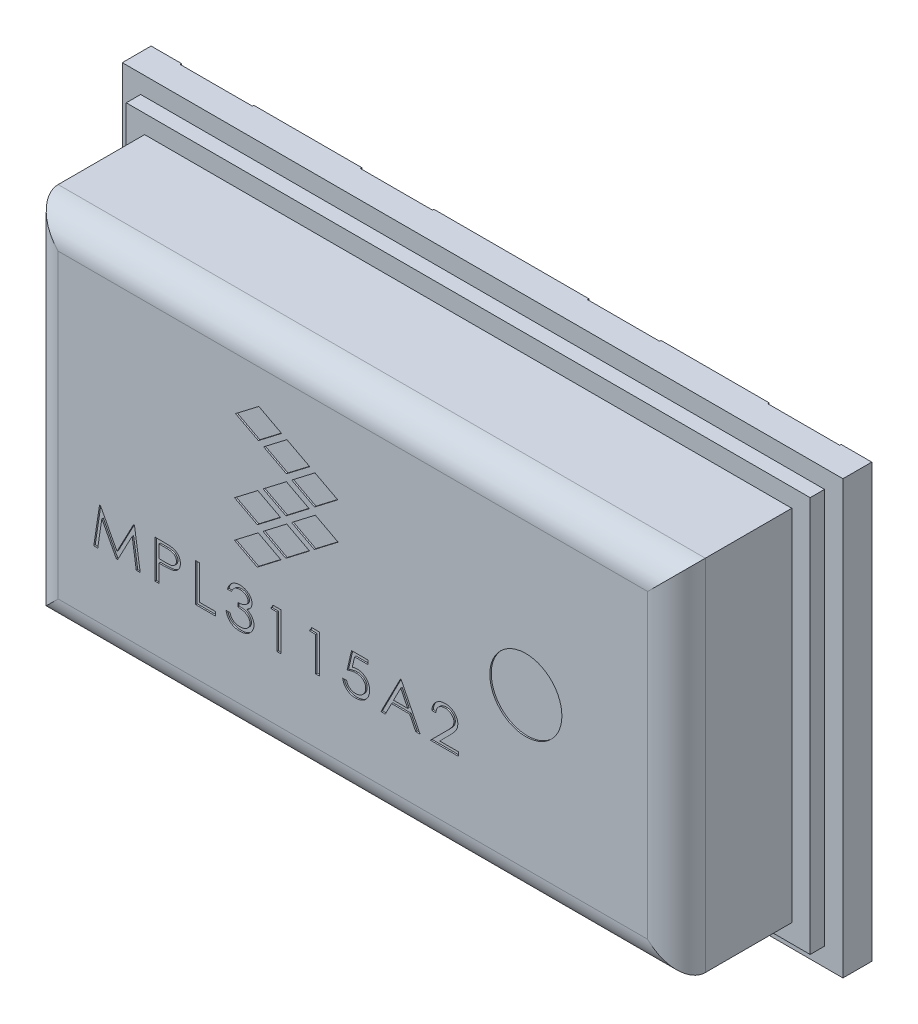
SolidWorks part; units mm, degrees
ref_plane "Plan de face" through (0, 0, 0) normal (0, 0, 1) x (1, 0, 0)
ref_plane "Plan de dessus" through (0, 0, 0) normal (0, 1, 0) x (1, 0, 0)
ref_plane "Plan de droite" through (0, 0, 0) normal (1, 0, 0) x (0, 0, -1)
sketch "Esquisse1" plane through (0, 0, 0) normal (0, 0, 1) x (1, 0, 0)
  line L1 (-2.5, 1.5) -> (2.5, 1.5)
  line L2 (-2.5, 1.5) -> (-2.5, -1.5)
  line L3 (-2.5, -1.5) -> (2.5, -1.5)
  line L4 (2.5, 1.5) -> (2.5, -1.5)
  line L5 (-2.5, 1.5) -> (2.5, -1.5) construction
  line L6 (-2.5, -1.5) -> (2.5, 1.5) construction
  point P0 (0, 0)
  dimension "D1" = 5
  dimension "D2" = 3
extrude "Boss.-Extru.1" add sketch "Esquisse1" along normal blind 1.1
sketch "Esquisse2" plane through (0, 0, 1.1) normal (0, 0, 1) x (1, 0, 0)
  line L9 (-2.7738, 1.6504) -> (2.6901, 1.6504)
  line L10 (-2.7738, 1.6504) -> (-2.7738, -1.6643)
  line L11 (-2.7738, -1.6643) -> (2.6901, -1.6643)
  line L12 (2.245, -1.245) -> (2.245, 1.245)
  line L13 (2.245, 1.245) -> (-2.245, 1.245)
  line L14 (-2.245, 1.245) -> (-2.245, -1.245)
  line L15 (-2.245, -1.245) -> (2.245, -1.245)
  line L16 (2.245, -1.245) -> (2.245, 1.245)
  line L17 (2.245, 1.245) -> (-2.245, 1.245)
  line L18 (-2.245, 1.245) -> (-2.245, -1.245)
  line L19 (-2.245, -1.245) -> (2.245, -1.245)
  line L20 (2.6901, 1.6504) -> (2.6901, -1.6643)
  dimension "D1" = 0.255
extrude "Enlèv. mat.-Extru.1" cut sketch "Esquisse2" against normal blind 0.8
sketch "Esquisse3" plane through (0, 0, 0.3) normal (0, 0, 1) x (1, 0, 0)
  line L6 (3.0551, -1.9915) -> (-3.0582, -1.9915)
  line L7 (3.0551, -1.9915) -> (3.0551, 1.8673)
  line L8 (2.3725, -1.3725) -> (2.3725, 1.3725)
  line L9 (2.3725, 1.3725) -> (-2.3725, 1.3725)
  line L10 (-2.3725, 1.3725) -> (-2.3725, -1.3725)
  line L11 (-2.3725, -1.3725) -> (2.3725, -1.3725)
  line L12 (2.3725, -1.3725) -> (2.3725, 1.3725)
  line L13 (2.3725, 1.3725) -> (-2.3725, 1.3725)
  line L14 (-2.3725, 1.3725) -> (-2.3725, -1.3725)
  line L15 (-2.3725, -1.3725) -> (2.3725, -1.3725)
  line L16 (3.0551, 1.8673) -> (-3.0582, 1.8673)
  line L17 (-3.0582, -1.9915) -> (-3.0582, 1.8673)
  dimension "D1" = 0.1275
extrude "Enlèv. mat.-Extru.2" cut sketch "Esquisse3" against normal blind 0.1
fillet "Congé1" radius 0.2 4 edges at (0, 1.245, 1.1) (2.245, 0, 1.1) (0, -1.245, 1.1) (-2.245, 0, 1.1)
sketch "Esquisse4" plane through (0, 0, 1.1) normal (0, 0, 1) x (1, 0, 0)
  line L0 (-1.8215, -0.6018) -> (1.7734, -0.6018) construction
  line L1 (-2.045, 0) -> (2.045, 0) construction
  line L2 (-2.045, 1.045) -> (-2.045, -1.045) construction
  line L3 (2.045, -1.045) -> (2.045, 1.045) construction
  line L4 (2.5, -1.5) -> (2.5, 1.5) construction
  circle A0 centre (1.2, 0) radius 0.25
  text T0 "MPL3115A2" font "Century Gothic" height in points 1
  dimension "D1" = 0.5
  dimension "D2" = 1.3
extrude "Enlèv. mat.-Extru.3" cut sketch "Esquisse4" against normal blind 0.01
sketch "Esquisse5" plane through (0, 0, 1.1) normal (0, 0, 1) x (1, 0, 0)
  line L0 (-0.4243, 0.4799) -> (-0.2661, 0.3969)
  line L1 (-0.4243, 0.4799) -> (-0.2632, 0.6036)
  line L2 (-0.2661, 0.3969) -> (-0.105, 0.5206)
  line L3 (-0.2632, 0.6036) -> (-0.105, 0.5206)
extrude "Enlèv. mat.-Extru.4" cut sketch "Esquisse5" against normal blind 0.01
pattern_linear "Répétition linéaire5" count 3 spacing 0.22 along (-0.8856, 0.4644, 0) of "Enlèv. mat.-Extru.4"
pattern_linear "Répétition linéaire6" count 3 spacing 0.25 along (-0.7932, -0.609, 0) of "Enlèv. mat.-Extru.4"
sketch "Esquisse10" plane through (0, 0, 1.1) normal (0, 0, 1) x (1, 0, 0)
  line L0 (-0.4253, 0.2242) -> (-0.2671, 0.1412)
  line L1 (-0.4253, 0.2242) -> (-0.2607, 0.3506)
  line L2 (-0.2671, 0.1412) -> (-0.1025, 0.2676)
  line L3 (-0.2607, 0.3506) -> (-0.1025, 0.2676)
  line L4 (-0.6226, 0.3276) -> (-0.4644, 0.2447) construction
  line L5 (-0.4644, 0.2447) -> (-0.3033, 0.3683) construction
  dimension "D1" = 0.1622
  dimension "D2" = 0.04
extrude "Enlèv. mat.-Extru.6" cut sketch "Esquisse10" against normal blind 0.01
pattern_linear "Répétition linéaire7" count 3 spacing 0.25 along (-0.7932, -0.609, 0) of "Enlèv. mat.-Extru.6"
sketch "Esquisse11" plane through (0, 0, 0) normal (0, 0, -1) x (-1, 0, 0)
  line L0 (0, 1.5) -> (0, -1.5) construction
  line L1 (-2.5, 1.5) -> (2.5, 1.5) construction
  line L2 (2.5, -1.5) -> (-2.5, -1.5) construction
  line L3 (2.5, 0) -> (-2.5, 0) construction
  line L4 (2.5, 1.5) -> (2.5, -1.5) construction
  line L5 (-2.5, -1.5) -> (-2.5, 1.5) construction
  line L6 (2.0382, 0.7) -> (2.0382, 1.5) construction
  line L7 (1.7882, 1.5) -> (2.2882, 1.5)
  line L8 (1.7882, 1.5) -> (1.7882, 0.7)
  line L9 (1.7882, 0.7) -> (2.2882, 0.7)
  line L10 (2.2882, 1.5) -> (2.2882, 0.7)
  line L11 (1.7882, 1.1) -> (2.2882, 1.1) construction
  line L12 (0.5382, 1.5) -> (1.0382, 1.5)
  line L13 (0.5382, 1.5) -> (0.5382, 0.7)
  line L14 (0.5382, 0.7) -> (1.0382, 0.7)
  line L15 (1.0382, 1.5) -> (1.0382, 0.7)
  line L16 (0.7882, 0.7) -> (0.7882, 1.5) construction
  line L17 (0.5382, 1.1) -> (1.0382, 1.1) construction
  line L18 (0.5382, -1.1) -> (1.0382, -1.1) construction
  line L19 (0.7882, -0.7) -> (0.7882, -1.5) construction
  line L20 (1.7882, -1.1) -> (2.2882, -1.1) construction
  line L21 (2.0382, -0.7) -> (2.0382, -1.5) construction
  line L22 (1.0382, -1.5) -> (1.0382, -0.7)
  line L23 (0.5382, -0.7) -> (1.0382, -0.7)
  line L24 (0.5382, -1.5) -> (0.5382, -0.7)
  line L25 (0.5382, -1.5) -> (1.0382, -1.5)
  line L26 (2.2882, -1.5) -> (2.2882, -0.7)
  line L27 (1.7882, -0.7) -> (2.2882, -0.7)
  line L28 (1.7882, -1.5) -> (1.7882, -0.7)
  line L29 (1.7882, -1.5) -> (2.2882, -1.5)
  line L30 (-2.0382, -0.7) -> (-2.0382, -1.5) construction
  line L31 (-1.7882, -1.1) -> (-2.2882, -1.1) construction
  line L32 (-0.7882, -0.7) -> (-0.7882, -1.5) construction
  line L33 (-0.5382, -1.1) -> (-1.0382, -1.1) construction
  line L34 (-0.5382, 1.1) -> (-1.0382, 1.1) construction
  line L35 (-0.7882, 0.7) -> (-0.7882, 1.5) construction
  line L36 (-1.7882, 1.1) -> (-2.2882, 1.1) construction
  line L37 (-2.0382, 0.7) -> (-2.0382, 1.5) construction
  line L38 (-1.7882, -1.5) -> (-2.2882, -1.5)
  line L39 (-1.7882, -1.5) -> (-1.7882, -0.7)
  line L40 (-1.7882, -0.7) -> (-2.2882, -0.7)
  line L41 (-2.2882, -1.5) -> (-2.2882, -0.7)
  line L42 (-0.5382, -1.5) -> (-1.0382, -1.5)
  line L43 (-0.5382, -1.5) -> (-0.5382, -0.7)
  line L44 (-0.5382, -0.7) -> (-1.0382, -0.7)
  line L45 (-1.0382, -1.5) -> (-1.0382, -0.7)
  line L46 (-1.0382, 1.5) -> (-1.0382, 0.7)
  line L47 (-0.5382, 0.7) -> (-1.0382, 0.7)
  line L48 (-0.5382, 1.5) -> (-0.5382, 0.7)
  line L49 (-0.5382, 1.5) -> (-1.0382, 1.5)
  line L50 (-2.2882, 1.5) -> (-2.2882, 0.7)
  line L51 (-1.7882, 0.7) -> (-2.2882, 0.7)
  line L52 (-1.7882, 1.5) -> (-1.7882, 0.7)
  line L53 (-1.7882, 1.5) -> (-2.2882, 1.5)
  dimension "D1" = 0.8
  dimension "D2" = 0.5
  dimension "D3" = 2
extrude "Enlèv. mat.-Extru.7" cut sketch "Esquisse11" against normal blind 0.01
